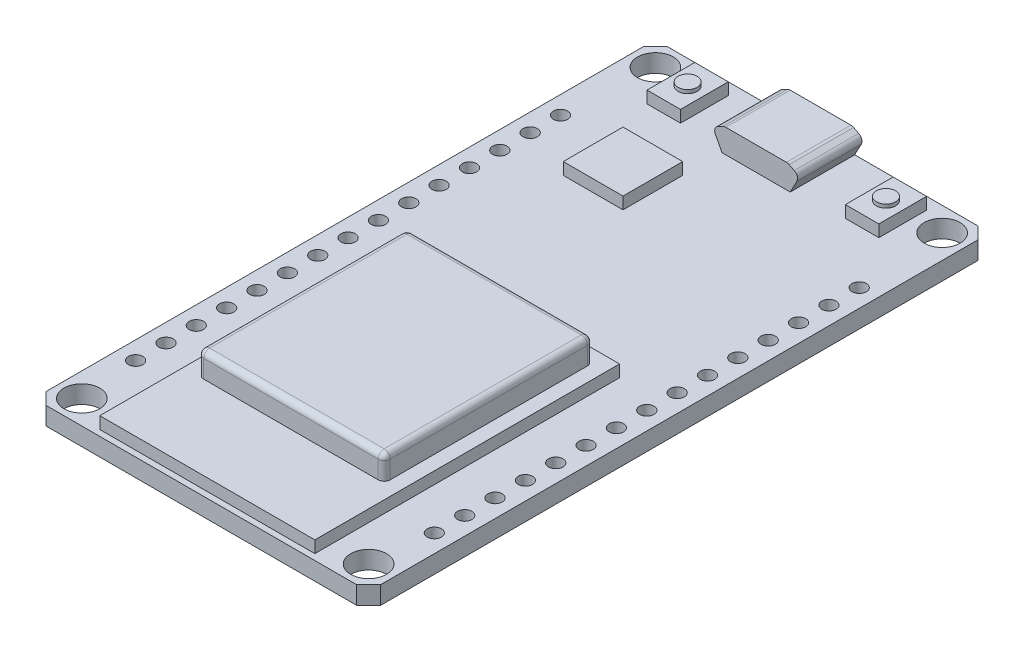
SolidWorks part; units mm, degrees
ref_plane "Plano frontal" through (0, 0, 0) normal (0, 0, 1) x (1, 0, 0)
ref_plane "Plano superior" through (0, 0, 0) normal (0, 1, 0) x (1, 0, 0)
ref_plane "Plano direito" through (0, 0, 0) normal (1, 0, 0) x (0, 0, -1)
sketch "Esboço2" plane through (0, 0, 0) normal (0, 1, 0) x (1, 0, 0)
  line L0 (-14, -25) -> (-13, -26)
  line L1 (-13, 26) -> (13, 26)
  line L2 (-14, 25) -> (-14, -25)
  line L3 (-13, -26) -> (13, -26)
  line L4 (14, 25) -> (14, -25)
  line L5 (-14, 26) -> (14, -26) construction
  line L6 (-14, -26) -> (14, 26) construction
  line L7 (-12, 24) -> (12, 24) construction
  line L8 (-12, 24) -> (-12, -24) construction
  line L9 (-12, -24) -> (12, -24) construction
  line L10 (12, 24) -> (12, -24) construction
  line L11 (13, -26) -> (14, -25)
  line L12 (-14, 25) -> (-13, 26)
  line L13 (13, 26) -> (14, 25)
  circle A0 centre (-12, 24) radius 1.5
  circle A1 centre (12, 24) radius 1.5
  circle A2 centre (-12, -24) radius 1.5
  circle A3 centre (12, -24) radius 1.5
  point P0 (0, 0)
  point P6 (0, 0)
  dimension "D7" = 3
  dimension "D1" = 52
  dimension "D2" = 28
  dimension "D3" = 2
  dimension "D4" = 2
  dimension "D5" = 2
  dimension "D6" = 2
extrude "Ressalto-extrusão1" add sketch "Esboço2" along normal blind 1.5
sketch "Esboço3" plane through (0, 1.5, 0) normal (0, 1, 0) x (1, 0, 0)
  line L0 (-13, -26) -> (13, -26) construction
  line L1 (-9, 0) -> (9, 0)
  line L2 (-9, 0) -> (-9, -25.5)
  line L3 (-9, -25.5) -> (9, -25.5)
  line L4 (9, 0) -> (9, -25.5)
  line L5 (-9, 0) -> (9, -25.5) construction
  line L6 (-9, -25.5) -> (9, 0) construction
  point P0 (0, -12.75)
  dimension "D1" = 18
  dimension "D2" = 25.5
  dimension "D3" = 0.5
extrude "Ressalto-extrusão2" add sketch "Esboço3" along normal blind 1
sketch "Esboço4" plane through (0, 2.5, 0) normal (0, 1, 0) x (1, 0, 0)
  line L0 (9, 0) -> (-9, 0) construction
  line L1 (-7.8, -1) -> (7.8, -1)
  line L2 (-7.8, -1) -> (-7.8, -18.5)
  line L3 (-7.8, -18.5) -> (7.8, -18.5)
  line L4 (7.8, -1) -> (7.8, -18.5)
  line L5 (-7.8, -1) -> (7.8, -18.5) construction
  line L6 (-7.8, -18.5) -> (7.8, -1) construction
  point P0 (0, -9.75)
  dimension "D1" = 17.5
  dimension "D2" = 15.6
  dimension "D3" = 1
extrude "Ressalto-extrusão3" add sketch "Esboço4" along normal blind 2
sketch "Esboço5" plane through (0, 1.5, 0) normal (0, 1, 0) x (1, 0, 0)
  line L0 (13, 26) -> (-13, 26) construction
  line L1 (-8.0236, 17.3129) -> (-3.0236, 17.3129)
  line L2 (-8.0236, 17.3129) -> (-8.0236, 12.3129)
  line L3 (-8.0236, 12.3129) -> (-3.0236, 12.3129)
  line L4 (-3.0236, 17.3129) -> (-3.0236, 12.3129)
  line L17 (-9.7, 25) -> (-6.9, 25)
  line L18 (-9.7, 25) -> (-9.7, 21)
  line L19 (-9.7, 21) -> (-6.9, 21)
  line L20 (-6.9, 25) -> (-6.9, 21)
  line L21 (-14, 25) -> (-14, -25) construction
  line L22 (0, 0) -> (0, 26) construction
  line L23 (9, 0) -> (-9, 0) construction
  line L24 (6.9, 25) -> (6.9, 21)
  line L25 (9.7, 21) -> (6.9, 21)
  line L26 (9.7, 25) -> (9.7, 21)
  line L27 (9.7, 25) -> (6.9, 25)
  dimension "D1" = 5
  dimension "D2" = 4
  dimension "D3" = 2.8
  dimension "D4" = 1
  dimension "D5" = 4.3
extrude "Ressalto-extrusão4" add sketch "Esboço5" along normal blind 1
sketch "Esboço6" plane through (0, 2.5, 0) normal (0, 1, 0) x (1, 0, 0)
  line L0 (6.9, 25) -> (9.7, 21) construction
  line L1 (-9.7, 25) -> (-6.9, 21) construction
  line L2 (-6.9, 21) -> (-6.9, 25) construction
  line L3 (-6.9, 21) -> (-6.9, 25) construction
  circle A0 centre (-8.3, 23) radius 0.8
  circle A1 centre (8.3, 23) radius 0.8
  point P16 (-8.3, 23)
  point P18 (8.3, 23)
  dimension "D1" = 1.6
extrude "Ressalto-extrusão5" add sketch "Esboço6" along normal blind 0.3
sketch "Esboço7" plane through (0, 0, -26) normal (0, 0, -1) x (-1, 0, 0)
  line L3 (3.0173, 1.5) -> (-2.6827, 1.5)
  line L4 (-13, 1.5) -> (13, 1.5) construction
  line L5 (-2.6827, 1.5) -> (-3.2417, 2.548)
  line L6 (-3.0251, 3.2301) -> (-2.5941, 3.4467)
  line L7 (-2.3695, 3.5) -> (2.7041, 3.5)
  line L8 (0.1673, 3.5) -> (0.1673, 1.5) construction
  line L9 (3.3596, 3.2301) -> (2.9286, 3.4467)
  line L10 (3.0173, 1.5) -> (3.5762, 2.548)
  arc A0 (-2.5941, 3.4467) -> (-2.3695, 3.5) centre (-2.3695, 3) cw
  arc A1 (2.9286, 3.4467) -> (2.7041, 3.5) centre (2.7041, 3) ccw
  arc A2 (3.3596, 3.2301) -> (3.5762, 2.548) centre (3.135, 2.7833) cw
  arc A3 (-3.2417, 2.548) -> (-3.0251, 3.2301) centre (-2.8005, 2.7833) cw
  point P14 (-2.4881, 3.5)
  point P17 (2.8227, 3.5)
  point P20 (3.8173, 3)
  point P23 (-3.4827, 3)
  dimension "D5" = 0.5
  dimension "D1" = 2
  dimension "D2" = 0.8
  dimension "D3" = 3.65
  dimension "D4" = 0.5
extrude "Ressalto-extrusão6" add sketch "Esboço7" against normal blind 5.4
sketch "Esboço8" plane through (0, 0, -26) normal (0, 0, -1) x (-1, 0, 0)
  line L0 (-9, 1.5) -> (9, 1.5) construction
  line L1 (-3.9106, 1.5) -> (3.7324, 1.5)
  line L2 (-3.9106, 1.5) -> (-3.9106, 4.1101)
  line L3 (-3.9106, 4.1101) -> (3.7324, 4.1101)
  line L4 (3.7324, 1.5) -> (3.7324, 4.1101)
extrude "Corte-extrusão1" cut sketch "Esboço8" against normal blind 0.01
sketch "Esboço10" plane through (0, 0, -25.99) normal (0, 0, -1) x (-1, 0, 0)
  line L13 (2.7041, 3.1) -> (-2.3695, 3.1)
  line L14 (-2.4144, 3.0893) -> (-2.8454, 2.8727)
  line L15 (-2.8887, 2.7363) -> (-2.4427, 1.9)
  line L16 (-2.4427, 1.9) -> (2.7773, 1.9)
  line L17 (2.7773, 1.9) -> (3.2233, 2.7363)
  line L18 (3.18, 2.8727) -> (2.749, 3.0893)
  arc A8 (-2.3695, 3.1) -> (-2.4144, 3.0893) centre (-2.3695, 3) ccw
  arc A9 (-2.8454, 2.8727) -> (-2.8887, 2.7363) centre (-2.8005, 2.7833) ccw
  arc A10 (3.2233, 2.7363) -> (3.18, 2.8727) centre (3.135, 2.7833) ccw
  arc A11 (2.749, 3.0893) -> (2.7041, 3.1) centre (2.7041, 3) ccw
extrude "Corte-extrusão2" cut sketch "Esboço10" against normal blind 5
sketch "Esboço11" plane through (0, 1.5, 0) normal (0, 1, 0) x (1, 0, 0)
  line L0 (-13, -26) -> (13, -26) construction
  line L1 (-14, 25) -> (-14, -25) construction
  line L2 (0, 0) -> (0, -25.5) construction
  line L3 (-9, -25.5) -> (9, -25.5) construction
  circle A0 centre (-12.5, 16.56) radius 0.6
  circle A1 centre (-12.5, 14.02) radius 0.6
  circle A2 centre (-12.5, 11.48) radius 0.6
  circle A3 centre (-12.5, 8.94) radius 0.6
  circle A4 centre (-12.5, 6.4) radius 0.6
  circle A5 centre (-12.5, 3.86) radius 0.6
  circle A6 centre (-12.5, 1.32) radius 0.6
  circle A7 centre (-12.5, -1.22) radius 0.6
  circle A8 centre (-12.5, -3.76) radius 0.6
  circle A9 centre (-12.5, -6.3) radius 0.6
  circle A10 centre (-12.5, -8.84) radius 0.6
  circle A11 centre (-12.5, -11.38) radius 0.6
  circle A12 centre (-12.5, -13.92) radius 0.6
  circle A13 centre (-12.5, -16.46) radius 0.6
  circle A14 centre (-12.5, -19) radius 0.6
  circle A15 centre (12.5, -19) radius 0.6
  circle A16 centre (12.5, -16.46) radius 0.6
  circle A17 centre (12.5, -13.92) radius 0.6
  circle A18 centre (12.5, -11.38) radius 0.6
  circle A19 centre (12.5, -8.84) radius 0.6
  circle A20 centre (12.5, -6.3) radius 0.6
  circle A21 centre (12.5, -3.76) radius 0.6
  circle A22 centre (12.5, -1.22) radius 0.6
  circle A23 centre (12.5, 1.32) radius 0.6
  circle A24 centre (12.5, 3.86) radius 0.6
  circle A25 centre (12.5, 6.4) radius 0.6
  circle A26 centre (12.5, 8.94) radius 0.6
  circle A27 centre (12.5, 11.48) radius 0.6
  circle A28 centre (12.5, 14.02) radius 0.6
  circle A29 centre (12.5, 16.56) radius 0.6
  dimension "D1" = 1.2
  dimension "D3" = 7
  dimension "D4" = 1.5
  dimension "D2" = 15
extrude "Corte-extrusão3" cut sketch "Esboço11" against normal blind 5
fillet "Filete1" radius 0.5 8 edges at (-7.8, 3.5, 1) (7.8, 3.5, 18.5) (0, 4.5, 18.5) (-7.8, 3.5, 18.5) (-7.8, 4.5, 9.75) (7.8, 3.5, 1) (0, 4.5, 1) (7.8, 4.5, 9.75)
